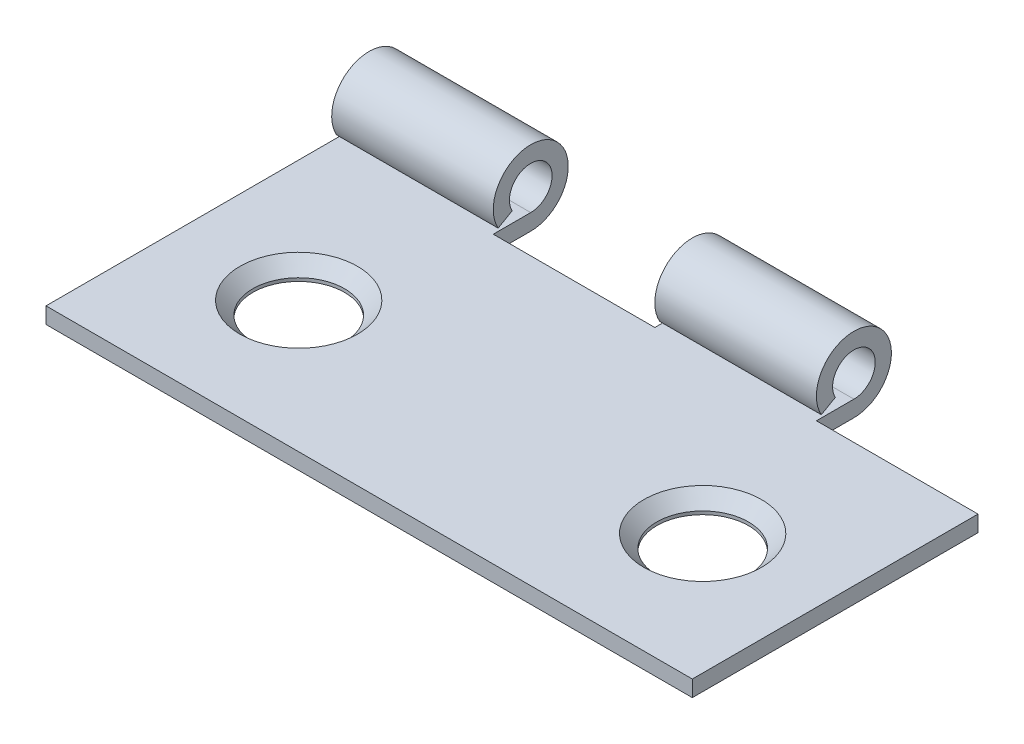
SolidWorks part; units mm, degrees
ref_plane "Front Plane" through (0, 0, 0) normal (0, 0, 1) x (1, 0, 0)
ref_plane "Top Plane" through (0, 0, 0) normal (0, 1, 0) x (1, 0, 0)
ref_plane "Right Plane" through (0, 0, 0) normal (1, 0, 0) x (0, 0, -1)
sketch "Sketch1" plane through (0, 0, 0) normal (0, 1, 0) x (1, 0, 0)
  line L0 (-12.7, 0) -> (12.7, 0) construction
  line L1 (-12.7, -12.7) -> (-12.7, 12.7) construction
  line L2 (-12.7, -12.7) -> (-7.9248, -12.7) construction
  line L4 (-7.9248, -12.7) -> (7.9502, -12.7) construction
  line L5 (12.7254, -12.7) -> (12.7254, -7.5438) construction
  line L6 (7.9502, -12.7) -> (12.7254, -12.7) construction
  line L7 (-12.7, 12.7) -> (-7.9248, 12.7) construction
  line L8 (-7.9248, 12.7) -> (7.9502, 12.7) construction
  line L9 (7.9502, 12.7) -> (23.8252, 12.7) construction
  line L10 (23.8252, 12.7) -> (28.6004, 12.7) construction
  line L11 (7.9502, -9.8552) -> (7.9502, -5.2324) construction
  line L12 (7.9502, -7.5438) -> (12.7254, -7.5438) construction
  point P3 (7.9502, -9.3472)
  point P4 (0, 0)
  point P8 (-12.7, 0)
  point P17 (-6.35, 0)
  point P21 (7.9502, -7.5438)
  dimension "Frame Leaf Height" = 25.4
  dimension "Overall Width" = 25.4
  dimension "Hole to End 1" = 4.7752
  dimension "Hole to End 2" = 4.7752
  dimension "D1" = 4.7752
  dimension "D2" = 4.7752
  dimension "D4" = 15.875
  dimension "D6" = 15.875
  dimension "Knuckle Length" = 6.35
  dimension "Hole Chamfer Dia" = 4.6228
  dimension "Hole Center to Pin" = 7.5438
  dimension "Door Leaf Height" = 25.4254
  dimension "Mounting Hole Diameter" = 3.6068
  dimension "D3" = 15.875
  dimension "Frame Leaf Width" = 12.7
  dimension "Door Leaf Width" = 12.7
sketch "Sketch2" plane through (0, 0, 0) normal (1, 0, 0) x (0, 0, -1)
  line L2 (0, -1.4732) -> (0, -0.8382) construction
  line L4 (0, 0.8382) -> (0, -0.8382) construction
  point P8 (0, 0)
  dimension "Leaf Thickness" = 0.635
  dimension "Pin Diameter" = 1.6764
sketch "Sketch3" plane through (0, 0, 0) normal (1, 0, 0) x (0, 0, -1)
  line L3 (0, 0) -> (-1.4732, -0.8382) construction
  line L4 (0, -1.4732) -> (-12.7, -1.4732)
  line L5 (-12.7, -1.4732) -> (-12.7, -0.8382)
  line L7 (-12.7, -0.8382) -> (0, -0.8382)
  line L8 (-12.7, 0) -> (12.7, 0) construction
  line L9 (-0.7285, -0.4145) -> (-1.2805, -0.7285)
  line L11 (-1.4732, 0) -> (-1.4732, -0.8382) construction
  circle A4 centre (0, 0) radius 0.8382 construction
  circle A5 centre (0, 0) radius 1.4732 construction
  arc A8 (-0.7285, -0.4145) -> (0, -0.8382) centre (0, 0) cw
  arc A9 (-1.2805, -0.7285) -> (0, -1.4732) centre (0, 0) cw
  point P0 (-1.2805, -0.7285)
  point P13 (-0.7285, -0.4145)
extrude "Boss-Extrude1" add sketch "Sketch3" along normal mid plane 25.4
sketch "Sketch4" plane through (0, 0, 0) normal (0, 1, 0) x (1, 0, 0)
  line L0 (-12.7, -1.4732) -> (12.7, -1.4732) construction
  line L1 (-12.7, -1.4732) -> (12.7, -1.4732) construction
  line L2 (12.7, 1.4732) -> (-12.7, 1.4732) construction
  line L3 (12.7, 1.4732) -> (-12.7, 1.4732) construction
  line L4 (-6.35, -1.4732) -> (-6.35, 1.4732)
  line L6 (-6.35, 1.4732) -> (0, 1.4732)
  line L7 (0, -1.4732) -> (-6.35, -1.4732)
  line L8 (0, 1.4732) -> (0, -1.4732)
  point P8 (-6.35, 0)
  dimension "D1" = 6.35
extrude "Cut-Extrude1" cut sketch "Sketch4" against normal through all both and the other way through all
pattern_linear "LPattern1" count 6 spacing 12.7 along (1, 0, 0) of "Cut-Extrude1"
sketch "Sketch5" plane through (0, -0.8382, 0) normal (0, 1, 0) x (1, 0, 0)
  line L0 (7.9502, -7.5438) -> (-7.9248, -7.5438) construction
  line L1 (0, -7.5438) -> (0, -12.7) construction
  line L2 (-7.9248, -7.5438) -> (-7.9248, -12.7) construction
  line L3 (12.7, -12.7) -> (-12.7, -12.7) construction
  circle A0 centre (7.9502, -7.5438) radius 2.3114
  circle A2 centre (-7.9248, -7.5438) radius 2.3114
extrude "Cut-Extrude2" cut sketch "Sketch5" against normal through all draft 45
sketch "Sketch9" plane through (0, 0, 0) normal (0, 1, 0) x (1, 0, 0)
  circle A0 centre (7.9502, -7.5438) radius 1.8034
  circle A2 centre (-7.9248, -7.5438) radius 1.8034
  dimension "D1" = 3.6068
extrude "Cut-Extrude3" cut sketch "Sketch9" against normal through all both and the other way through all
equation "\"Hole Chamfer Dia@Sketch1\"=\"Mounting Hole Diameter@Sketch1\"+.04"
equation "\"D1@Sketch9\"=\"Mounting Hole Diameter@Sketch1\""
equation "\"Hole to End 2@Sketch1\"=\"Hole to End 1@Sketch1\""
equation "\"Knuckle Length@Sketch1\"=\"Frame Leaf Height@Sketch1\" / 4"
equation "\"D3@Sketch7\"=\"Leaf Thickness@Sketch2\""
equation "\"D2@Sketch7\"=\"Overall Width@Sketch1\""
equation "\"D1@Sketch7\"=\"Pin Diameter@Sketch2\""
equation "\"D1@Boss-Extrude2\" = \"Frame Leaf Height@Sketch1\""
equation "\"D1@Sketch6\"=\"Pin Diameter@Sketch2\""
equation "\"D3@LPattern1\"=\"Knuckle Length@Sketch1\"*2"
equation "\"D1@Sketch4\"=\"Knuckle Length@Sketch1\""
equation "\"D1@Boss-Extrude1\" = \"Frame Leaf Height@Sketch1\""
equation "\"D6@Sketch1\"=\"D4@Sketch1\""
equation "\"D2@Sketch1\"=\"Hole to End 2@Sketch1\""
equation "\"D1@Sketch1\"=\"Hole to End 1@Sketch1\""
